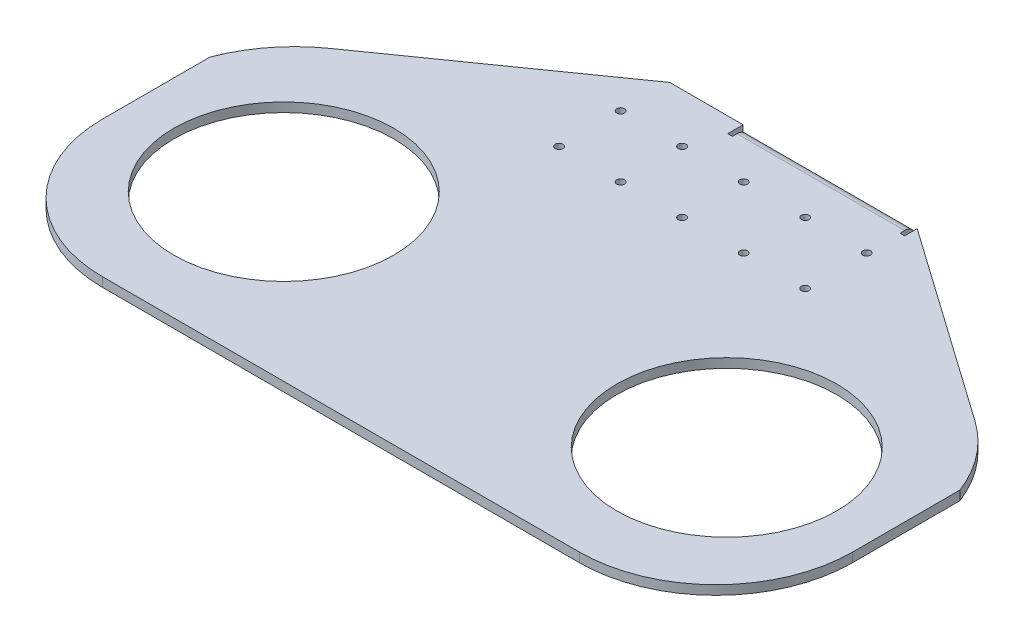
SolidWorks part; units mm, degrees
ref_plane "Спереди" through (0, 0, 0) normal (0, 0, 1) x (1, 0, 0)
ref_plane "Сверху" through (0, 0, 0) normal (0, 1, 0) x (1, 0, 0)
ref_plane "Справа" through (0, 0, 0) normal (1, 0, 0) x (0, 0, -1)
ref_plane "Плоскость4" through (0, 148.5, 0) normal (0, -1, 0) x (1, 0, 0)
sketch "Эскиз1" plane through (0, 148.5, 0) normal (0, -1, 0) x (1, 0, 0)
  line L0 (121.9, -25.8787) -> (121.9, 53.4)
  line L1 (121.9, 53.4) -> (-121.9, 53.4)
  line L2 (-121.9, 53.4) -> (-121.9, -25.8787)
  line L3 (-104.8475, -47.8377) -> (-40, -93.5)
  line L4 (-40, -93.5) -> (39.8416, -93.5)
  line L5 (39.8416, -93.5) -> (39.8416, -88.5)
  line L6 (39.8416, -88.5) -> (41.3416, -88.5)
  line L7 (41.3416, -88.5) -> (41.3416, -92.5553)
  line L8 (41.3416, -92.5553) -> (104.8475, -47.8377)
  arc A0 (104.8475, -47.8377) -> (121.9, -25.8787) centre (77.5, -9) ccw
  arc A1 (-121.9, -25.8787) -> (-104.8475, -47.8377) centre (-77.5, -9) ccw
extrude "Бобышка-Вытянуть1" add sketch "Эскиз1" against normal blind 3
sketch "Эскиз2" plane through (0, 151.5, 0) normal (0, 1, 0) x (-1, 0, 0)
  line L0 (14.6584, -93.5) -> (16.1584, -93.5)
  line L1 (16.1584, -93.5) -> (16.1584, -88.5)
  line L2 (16.1584, -88.5) -> (14.6584, -88.5)
  line L3 (14.6584, -88.5) -> (14.6584, -93.5)
extrude "Вырез-Вытянуть1" cut sketch "Эскиз2" against normal through all
sketch "Эскиз3" plane through (0, 148.5, 0) normal (0, -1, 0) x (1, 0, 0)
  line L0 (-14.6584, -90.5) -> (39.8416, -90.5)
  line L1 (39.8416, -90.5) -> (39.8416, -93.5)
  line L2 (39.8416, -93.5) -> (-14.6584, -93.5)
  line L3 (-14.6584, -93.5) -> (-14.6584, -90.5)
extrude "Бобышка-Вытянуть2" add sketch "Эскиз3" along normal blind 40
hole_wizard "Диаметр отверстия Ø2.5 (2.5)1" positions "Эскиз5" profile "Эскиз4" hole size "Ø2.5" standard "Ansi Metric"
sketch "Эскиз5" plane through (0, 148.5, 0) normal (0, -1, 0) x (-1, 0, 0)
  point P0 (40, 57.5)
  point P1 (40, 77.5)
  point P2 (20, 57.5)
  point P3 (20, 77.5)
  point P4 (-40, 57.5)
  point P5 (-40, 77.5)
  point P6 (-20, 57.5)
  point P7 (-20, 77.5)
  point P8 (0, 57.5)
  point P9 (0, 77.5)
sketch "Эскиз4" plane through (-40, 148.5, -57.5) normal (1, 0, 0) x (0, 0, -1)
  line L0 (0, 0) -> (0, 3)
  line L1 (0, 3) -> (1.25, 3)
  line L2 (1.25, 3) -> (1.25, 0)
  line L5 (1.25, 0) -> (0, 0)
  line L11 (0, -6.35) -> (0, 107.95) construction
  dimension "Диаметр сквозного отверстия" = 2.5
  dimension "Глубина сквозного отверстия" = 3
hole_wizard "Диаметр отверстия Ø2.5 (2.5)2" positions "Эскиз7" profile "Эскиз6" hole size "Ø2.5" standard "Ansi Metric"
sketch "Эскиз7" plane through (0, 0, -90.5) normal (0, 0, 1) x (1, 0, 0)
  point P0 (25, 116.5)
  point P1 (25, 132.5)
  point P2 (0, 116.5)
  point P3 (0, 132.5)
sketch "Эскиз6" plane through (25, 116.5, -90.5) normal (1, 0, 0) x (0, -1, 0)
  line L0 (0, 0) -> (0, 3)
  line L1 (0, 3) -> (1.25, 3)
  line L2 (1.25, 3) -> (1.25, 0)
  line L5 (1.25, 0) -> (0, 0)
  line L11 (0, -6.35) -> (0, 107.95) construction
  dimension "Диаметр сквозного отверстия" = 2.5
  dimension "Глубина сквозного отверстия" = 3
hole_wizard "Отверстие с зазором M641" positions "Эскиз9" profile "Эскиз8" hole size "M64" standard "Ansi Metric"
sketch "Эскиз9" plane through (0, 148.5, 0) normal (0, -1, 0) x (-1, 0, 0)
  point P0 (72, 0)
  point P1 (-72, 0)
sketch "Эскиз8" plane through (-72, 148.5, 0) normal (1, 0, 0) x (0, 0, -1)
  line L0 (0, 0) -> (0, 3)
  line L1 (0, 3) -> (35.75, 3)
  line L2 (35.75, 3) -> (35.75, 0)
  line L5 (35.75, 0) -> (0, 0)
  line L11 (0, -6.35) -> (0, 107.95) construction
  dimension "Диаметр сквозного отверстия" = 71.5
  dimension "Глубина сквозного отверстия" = 3
fillet "Скругление1" radius 0.5 2 edges at (-40, 150, -93.5) (12.5916, 148.5, -90.5)
fillet "Скругление2" radius 3 2 edges at (39.8416, 108.5, -92) (-14.6584, 108.5, -92)
fillet "Скругление3" radius 3.5 1 edges at (12.5916, 151.5, -93.5)
fillet "Скругление4" radius 44.4 2 edges at (-121.9, 150, 53.4) (121.9, 150, 53.4)
